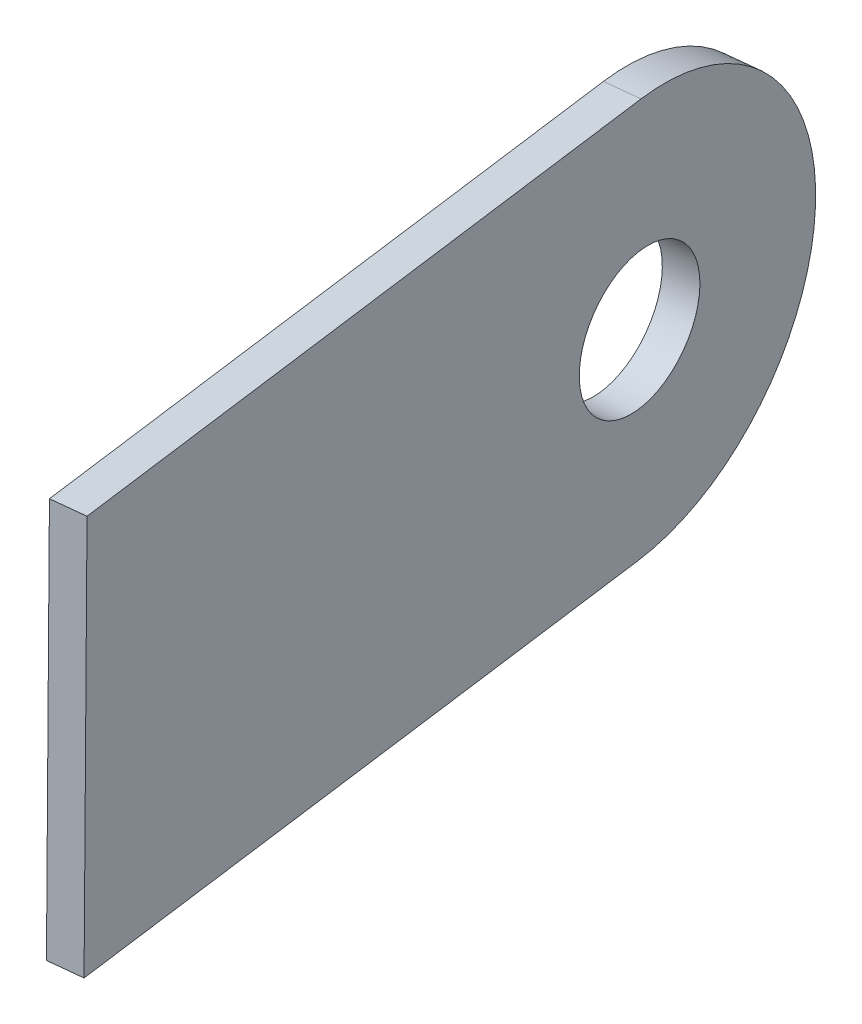
SolidWorks part; units mm, degrees
ref_plane "Front Plane" through (0, 0, 0) normal (0, 0, 1) x (1, 0, 0)
ref_plane "Top Plane" through (0, 0, 0) normal (0, 1, 0) x (1, 0, 0)
ref_plane "Right Plane" through (0, 0, 0) normal (1, 0, 0) x (0, 0, -1)
sketch "Sketch2" plane through (368.9369, -5.3839, -45.5872) normal (0.9923, -0.0145, -0.1226) x (-0.1226, 0.0018, -0.9925)
  line L0 (479.3638, 178.3451) -> (509.3347, 178.5941)
  line L1 (478.9871, 223.6738) -> (480.2153, 75.8596) construction
  line L2 (509.493, 159.5448) -> (479.522, 159.2958)
  line L3 (479.522, 159.2958) -> (479.3638, 178.3451)
  circle A0 centre (509.4139, 169.0695) radius 3.2639
  arc A1 (509.3347, 178.5941) -> (509.493, 159.5448) centre (509.4139, 169.0695) cw
  dimension "D1" = 6.5278
  dimension "D2" = 19.05
extrude "Boss-Extrude1" add sketch "Sketch2" along normal blind 1.5875
